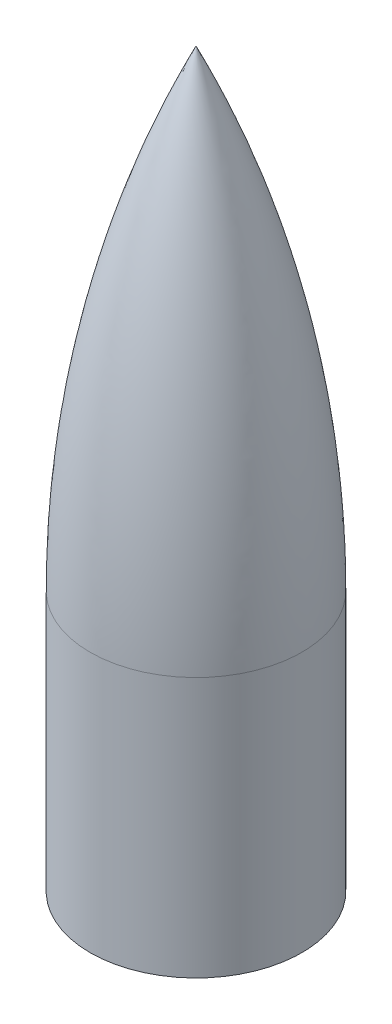
SolidWorks part; units mm, degrees
ref_plane "Plan de face" through (0, 0, 0) normal (0, 0, 1) x (1, 0, 0)
ref_plane "Plan de dessus" through (0, 0, 0) normal (0, 1, 0) x (1, 0, 0)
ref_plane "Plan de droite" through (0, 0, 0) normal (1, 0, 0) x (0, 0, -1)
sketch "Esquisse1" plane through (0, 0, 0) normal (0, 0, 1) x (1, 0, 0)
  line L0 (0, 0) -> (-2.85, 0)
  line L1 (-2.85, 0) -> (-2.85, 7)
  line L2 (0, 0) -> (0, 25.0706) construction
  line L3 (0, 19.7) -> (0, 0)
  line L4 (0, 0) -> (0, 36.4706) construction
  arc A0 (-2.85, 7) -> (0, 19.7) centre (26.8715, 7) cw
  dimension "D1" = 12.7
  dimension "D2" = 7
  dimension "D3" = 5.7
revolve "Révolution1" add sketch "Esquisse1" angle 360 about L2
equation "\"D3@Esquisse1\"=\"G1@Calibre.SLDASM\""
equation "\"D1@Esquisse1\"=\"Lballe@Calibre.SLDASM\""
